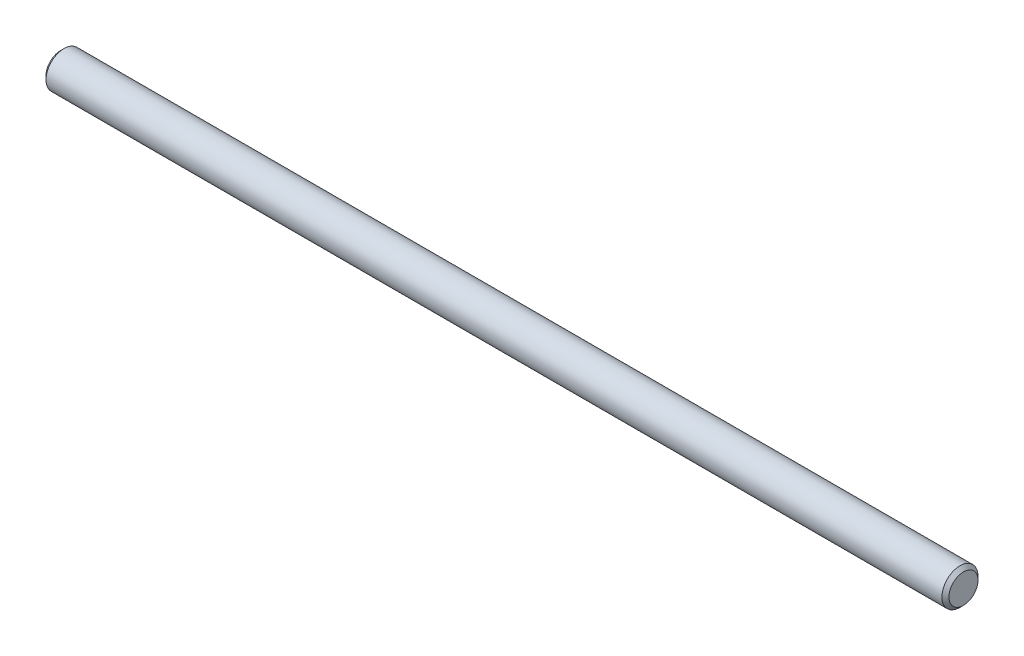
SolidWorks part; units mm, degrees
material "SUS304相当"
ref_plane "Front Plane" through (0, 0, 0) normal (0, 0, 1) x (1, 0, 0)
ref_plane "Top Plane" through (0, 0, 0) normal (0, 1, 0) x (1, 0, 0)
ref_plane "Right Plane" through (0, 0, 0) normal (1, 0, 0) x (0, 0, -1)
sketch "Sketch1" plane through (0, 0, 0) normal (0, 0, 1) x (1, 0, 0)
  line L0 (0, 0) -> (125, 0) construction
  line L1 (0, 0) -> (0, 2.01)
  line L2 (0, 2.01) -> (0.49, 2.5)
  line L3 (0.49, 2.5) -> (124.51, 2.5)
  line L4 (124.51, 2.5) -> (125, 2.01)
  line L5 (125, 2.01) -> (125, 0)
  line L6 (0, 0) -> (125, 0)
  dimension "L" = 125
  dimension "MSM_1" = 0.49
  dimension "FIX_1" = 45
  dimension "M" = 5
revolve "Revolve1" add sketch "Sketch1" angle 360 about L0
cosmetic thread "Thread1"
cosmetic thread "Thread2" [suppressed]
sketch "Sketch2" [suppressed] plane through (0, 0, 0) normal (0, 0, 1) x (1, 0, 0)
  line L1 (0, 0.5) -> (1, 0.5)
  line L2 (0, 0.5) -> (0, -0.5)
  line L3 (0, -0.5) -> (1, -0.5)
  line L4 (1, 0.5) -> (1, -0.5)
  dimension "W_1" = 1
extrude "Cut-Extrude1" [suppressed] cut sketch "Sketch2" against normal through all and the other way through all
ref_plane "Plane1" [suppressed] through (4, 0, 0) normal (1, 0, 0) x (0, 0, -1)
sketch "Sketch4" [suppressed] plane through (4, 0, 0) normal (1, 0, 0) x (0, 0, -1)
  line L1 (1.5, 1.3229) -> (1.5, -1.3229)
  line L2 (-1.5, 1.3229) -> (-1.5, -1.3229)
  arc A0 (-1.5, 1.3229) -> (-1.5, -1.3229) centre (0, 0) ccw
  arc A1 (1.5, -1.3229) -> (1.5, 1.3229) centre (0, 0) ccw
  dimension "S" = 3
extrude "Cut-Extrude2" [suppressed] cut sketch "Sketch4" along normal blind 3.5
equation "\"Factor\"= 1.082532"
equation "\"Pitch_M\"= IIF ( \"M\" = 30 , 3.5 , IIF ( \"M\" = 24 , 3 , IIF ( \"M\" = 22 , 2.5 , IIF ( \"M\" = 20 , 2.5 , IIF ( \"M\" = 18 , 2.5 , IIF ( \"M\" = 16 , 2 , IIF ( \"M\" = 14 , 2 , IIF ( \"M\" = 12 , 1.75 , IIF ( \"M\" = 10 , 1.5 , IIF ( \"M\" = 8 , 1.25 , IIF ( \"M\" = 6 , 1 , IIF ( \"M\" = 5 , 0.8 , IIF ( \"M\" = 4 , 0.7 , IIF ( \"M\" = 3 , 0.5 , IIF ( \"M\" = 2.6 , 0.45 , IIF ( \"M\" = 2.5 , 0.45 , 0.4 ) ) ) ) ) ) ) ) ) ) ) ) ) ) ) )"
equation "\"ATD_1\"= round ( \"M\" - \"Factor\" * \"Pitch_M\" , 3 )"
equation "\"Pitch_M1\"= IIF ( \"M\" = 30 , 1.5 , IIF ( \"M\" = 25 , 1.5 , IIF ( \"M\" = 20 , 1.5 , IIF ( \"M\" = 16 , 1.5 , IIF ( \"M\" = 15 , 1 , IIF ( \"M\" = 12 , 1.25 , IIF ( \"M\" = 10 , 1.25 , IIF ( \"M\" = 8 , 1 , IIF ( \"M\" = 6 , 0.75 , IIF ( \"M\" = 5 , 0.5 , IIF ( \"M\" = 4 , 0.5 , 0.35 ) ) ) ) ) ) ) ) ) ) )"
equation "\"ATD_2\"= round ( \"M\" - \"Factor\" * \"Pitch_M1\" , 3 )"
